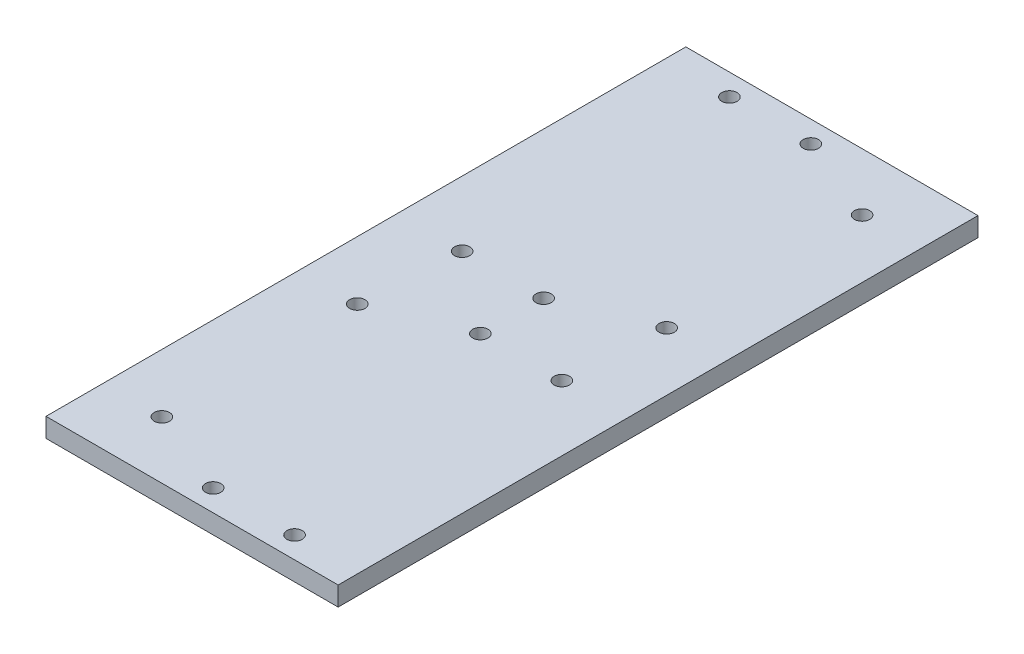
SolidWorks part; units mm, degrees
ref_plane "前视基准面" through (0, 0, 0) normal (0, 0, 1) x (1, 0, 0)
ref_plane "上视基准面" through (0, 0, 0) normal (0, 1, 0) x (1, 0, 0)
ref_plane "右视基准面" through (0, 0, 0) normal (1, 0, 0) x (0, 0, -1)
other "Configuration Table"
sketch "草图1" plane through (0, 0, 0) normal (0, 1, 0) x (1, 0, 0)
  line L1 (0, 0) -> (30.5, 0)
  line L2 (0, 0) -> (0, -66.8)
  line L3 (0, -66.8) -> (30.5, -66.8)
  line L4 (30.5, 0) -> (30.5, -66.8)
  circle A4 centre (6.8, -2.25) radius 0.8
  circle A5 centre (15.3, -2.25) radius 0.8
  circle A6 centre (15.2, -64.55) radius 0.8
  circle A7 centre (23.7, -64.55) radius 0.8
  circle A10 centre (6.8, -2.25) radius 1.3
  circle A11 centre (15.3, -2.25) radius 1.3
  circle A12 centre (15.2, -64.55) radius 1.3
  circle A13 centre (23.7, -64.55) radius 1.3
  circle A22 centre (24.4, -6) radius 1.3
  circle A23 centre (24.4, -26.4) radius 1.3
  circle A24 centre (6.8, -30.15) radius 1.3
  circle A25 centre (6.1, -60.8) radius 1.3
  circle A26 centre (23.7, -36.65) radius 1.3
  circle A27 centre (6.1, -40.4) radius 1.3
  circle A28 centre (15.2, -36.65) radius 1.3
  circle A29 centre (15.3, -30.15) radius 1.3
  circle A30 centre (24.4, -6) radius 0.8
  circle A31 centre (24.4, -26.4) radius 0.8
  circle A32 centre (6.1, -60.8) radius 0.8
  circle A33 centre (6.8, -30.15) radius 0.8
  circle A34 centre (6.1, -40.4) radius 0.8
  circle A35 centre (23.7, -36.65) radius 0.8
  circle A36 centre (15.3, -30.15) radius 0.8
  circle A37 centre (15.2, -36.65) radius 0.8
  point P33 (0, 0)
  point P35 (0, 0)
  point P37 (0, 0)
  point P39 (0, 0)
  point P40 (0, 0)
  point P41 (0, 0)
  point P43 (0, 0)
  point P45 (0, 0)
  point P47 (0, 0)
  point P49 (0, 0)
  point P51 (0, 0)
  dimension "D3" = 1.6
  dimension "D8" = 2.6
  dimension "D6" = 2.25
  dimension "D7" = 6.8
  dimension "D1" = 6.1
  dimension "D2" = 30.5
  dimension "D4" = 20.4
  dimension "D5" = 6
  dimension "D9" = 8.5
  dimension "D10" = 27.9
  dimension "D11" = 6.1
  dimension "32.4" = 66.8
  dimension "D12" = 6
  dimension "D13" = 20.4
  dimension "D14" = 2.25
  dimension "D15" = 6.8
  dimension "D16" = 8.5
  dimension "D17" = 27.9
extrude "凸台-拉伸1" add sketch "草图1" along normal blind 2
